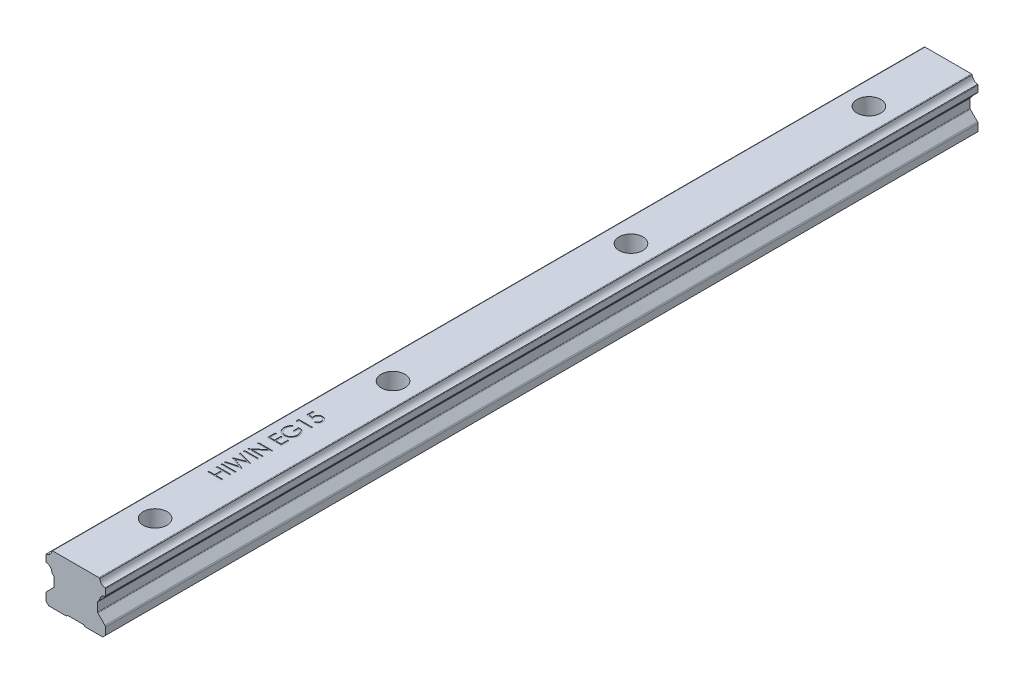
SolidWorks part; units mm, degrees
material "镀铬不锈钢"
ref_plane "前视基准面" through (0, 0, 0) normal (0, 0, 1) x (1, 0, 0)
ref_plane "上视基准面" through (0, 0, 0) normal (0, 1, 0) x (1, 0, 0)
ref_plane "右视基准面" through (0, 0, 0) normal (1, 0, 0) x (0, 0, -1)
sketch "草图1" plane through (0, 0, 0) normal (0, 0, 1) x (1, 0, 0)
  line L1 (7.5, 9.3694) -> (7.5, 10.8306)
  line L2 (5.8306, 12.5) -> (-5.8306, 12.5)
  line L3 (-7.5, 10.8306) -> (-7.5, 9.3694)
  line L4 (-6.0294, 7.6356) -> (-5.5879, 7.1941)
  line L5 (-5.5, 6.982) -> (-5.5, 4.8243)
  line L6 (-5.5879, 4.6121) -> (-7.3536, 2.8464)
  line L7 (-7.5, 2.4929) -> (-7.5, 0.7)
  line L8 (-7.5, 0.7) -> (-6.8, 0)
  line L9 (-6.8, 0) -> (-2.35, 0)
  line L10 (-2.35, 0) -> (-2.05, 0.3)
  line L11 (-2.05, 0.3) -> (2.05, 0.3)
  line L12 (2.05, 0.3) -> (2.35, 0)
  line L13 (2.35, 0) -> (6.8, 0)
  line L14 (6.8, 0) -> (7.5, 0.7)
  line L15 (7.5, 0.7) -> (7.5, 2.4929)
  line L16 (7.3536, 2.8464) -> (5.5879, 4.6121)
  line L17 (5.5, 4.8243) -> (5.5, 6.982)
  line L18 (5.5879, 7.1941) -> (6.0294, 7.6356)
  line L19 (-2.35, 0) -> (2.35, 0) construction
  line L20 (0, 0) -> (0, 12.5) construction
  arc A0 (7.5, 10.8306) -> (7.4215, 11.0328) centre (7.2, 10.8306) ccw
  arc A1 (6.0328, 12.4215) -> (7.4215, 11.0328) centre (7.529, 12.529) ccw
  arc A2 (6.0328, 12.4215) -> (5.8306, 12.5) centre (5.8306, 12.2) ccw
  arc A3 (-5.8306, 12.5) -> (-6.0328, 12.4215) centre (-5.8306, 12.2) ccw
  arc A4 (-7.4215, 11.0328) -> (-6.0328, 12.4215) centre (-7.529, 12.529) ccw
  arc A5 (-7.4215, 11.0328) -> (-7.5, 10.8306) centre (-7.2, 10.8306) ccw
  arc A6 (-7.5, 9.3694) -> (-7.4215, 9.1672) centre (-7.2, 9.3694) ccw
  arc A7 (-6.0294, 7.6356) -> (-7.4215, 9.1672) centre (-7.529, 7.671) ccw
  arc A8 (-5.5, 6.982) -> (-5.5879, 7.1941) centre (-5.8, 6.982) ccw
  arc A9 (-5.5879, 4.6121) -> (-5.5, 4.8243) centre (-5.8, 4.8243) ccw
  arc A10 (-7.3536, 2.8464) -> (-7.5, 2.4929) centre (-7, 2.4929) ccw
  arc A11 (7.5, 2.4929) -> (7.3536, 2.8464) centre (7, 2.4929) ccw
  arc A12 (5.5, 4.8243) -> (5.5879, 4.6121) centre (5.8, 4.8243) ccw
  arc A13 (5.5879, 7.1941) -> (5.5, 6.982) centre (5.8, 6.982) ccw
  arc A14 (7.4215, 9.1672) -> (6.0294, 7.6356) centre (7.529, 7.671) ccw
  arc A15 (7.4215, 9.1672) -> (7.5, 9.3694) centre (7.2, 9.3694) ccw
extrude "凸台-拉伸1" add sketch "草图1" against normal blind 220
hole_wizard "M3 六角凹头螺钉的柱形沉头孔1" positions "草图3" profile "草图2" counterbore size "M3" standard "ISO" end condition through all
sketch "草图3" plane through (1.3966, 12.5, 9.2217) normal (0, 1, 0) x (-1, 0, 0)
  point P0 (1.3966, -29.2217)
  dimension "D1" = 20
sketch "草图2" plane through (0, 12.5, -20) normal (1, 0, 0) x (0, 0, 1)
  line L0 (0, 0) -> (0, 12.5)
  line L1 (0, 12.5) -> (1.75, 12.5)
  line L3 (1.75, 12.5) -> (1.75, 4.5)
  line L4 (1.75, 4.5) -> (3, 4.5)
  line L5 (3, 4.5) -> (3, 0)
  line L7 (3, 0) -> (0, 0)
  line L11 (0, -6.35) -> (0, 107.95) construction
  dimension "通孔孔直径" = 3.5
  dimension "通孔孔深度" = 12.5
  dimension "柱形沉头孔直径" = 6
  dimension "柱形沉头孔深度" = 4.5
pattern_linear "阵列(线性)1" count 4 spacing 60 along (0, 0, -1) of "M3 六角凹头螺钉的柱形沉头孔1"
sketch "草图6" plane through (0, 12.5, 0) normal (0, 1, 0) x (1, 0, 0)
  line L0 (0, 20) -> (0, 80) construction
  text T0 "HIWIN EG15"
extrude "切除-拉伸1" cut sketch "草图6" against normal blind 0.1
equation "\"D1@凸台-拉伸1\" = 2 * \"D1@草图3\" + \"D3@阵列(线性)1\" *  ( \"D1@阵列(线性)1\"  - 1) "
